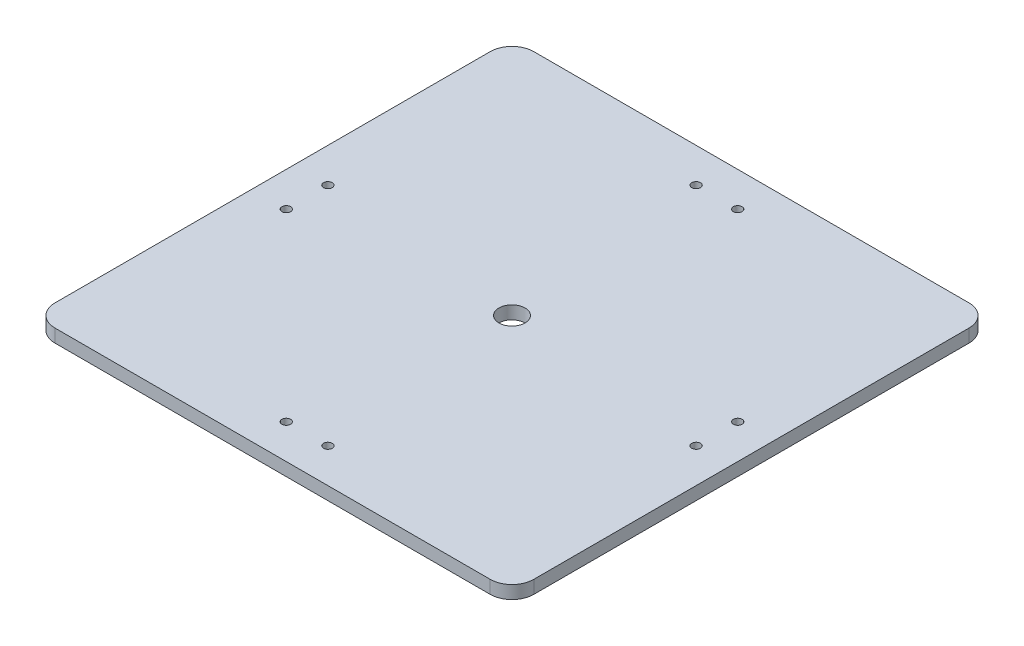
SolidWorks part; units mm, degrees
ref_plane "Front" through (0, 0, 0) normal (0, 0, 1) x (1, 0, 0)
ref_plane "Top" through (0, 0, 0) normal (0, 1, 0) x (1, 0, 0)
ref_plane "Right" through (0, 0, 0) normal (1, 0, 0) x (0, 0, -1)
sketch "Sketch1" plane through (0, 0, 0) normal (0, 1, 0) x (1, 0, 0)
  line L1 (110, -110) -> (-110, -110)
  line L2 (110, -110) -> (110, 110)
  line L3 (110, 110) -> (-110, 110)
  line L4 (-110, -110) -> (-110, 110)
  line L5 (0, 110) -> (0, -110) construction
  line L6 (110, 0) -> (-110, 0) construction
  point P0 (0, 0)
  dimension "D1" = 220
  dimension "D2" = 220
extrude "Boss-Extrude1" add sketch "Sketch1" along normal blind 6
sketch "Sketch2" plane through (0, 6, 0) normal (0, 1, 0) x (1, 0, 0)
  circle A0 centre (0, 0) radius 6
  dimension "D1" = 12
extrude "Cut-Extrude1" cut sketch "Sketch2" against normal blind 51
fillet "Fillet1" radius 10 4 edges at (-110, 3, -110) (-110, 3, 110) (110, 3, -110) (110, 3, 110)
sketch "Sketch3" plane through (0, 6, 0) normal (0, 1, 0) x (1, 0, 0)
  point P0 (-94.1527, -9.5579)
  point P1 (-94.1527, 9.5579)
  point P3 (-9.5579, 94.1527)
  point P5 (9.5579, 94.1527)
  point P7 (94.1527, 9.5579)
  point P9 (94.1527, -9.5579)
  point P11 (-9.5579, -94.1527)
  point P13 (9.5579, -94.1527)
hole_wizard "Ø4.0mm Dowel Hole1" positions "Sketch4" profile "Sketch5" hole size "Ø4.0" standard "ANSI Metric"
sketch "Sketch4" plane through (0, 6, 0) normal (0, 1, 0) x (1, 0, 0)
  point P0 (-9.5579, -94.1527)
  point P3 (9.5579, -94.1527)
  point P6 (94.1527, -9.5579)
  point P9 (94.1527, 9.5579)
  point P12 (9.5579, 94.1527)
  point P15 (-9.5579, 94.1527)
  point P18 (-94.1527, 9.5579)
  point P21 (-94.1527, -9.5579)
sketch "Sketch5" plane through (-9.5579, 6, 94.1527) normal (1, 0, 0) x (0, 0, 1)
  line L0 (0, 0) -> (0, 26.6017)
  line L1 (0, 26.6017) -> (2, 25.4)
  line L2 (2, 25.4) -> (2, 0)
  line L5 (2, 0) -> (0, 0)
  line L10 (0, 26.6017) -> (-2, 25.4) construction
  line L11 (0, -6.35) -> (0, 107.95) construction
  dimension "Hole Dia." = 4
  dimension "Hole Depth" = 25.4
  dimension "Drill Angle" = 118
